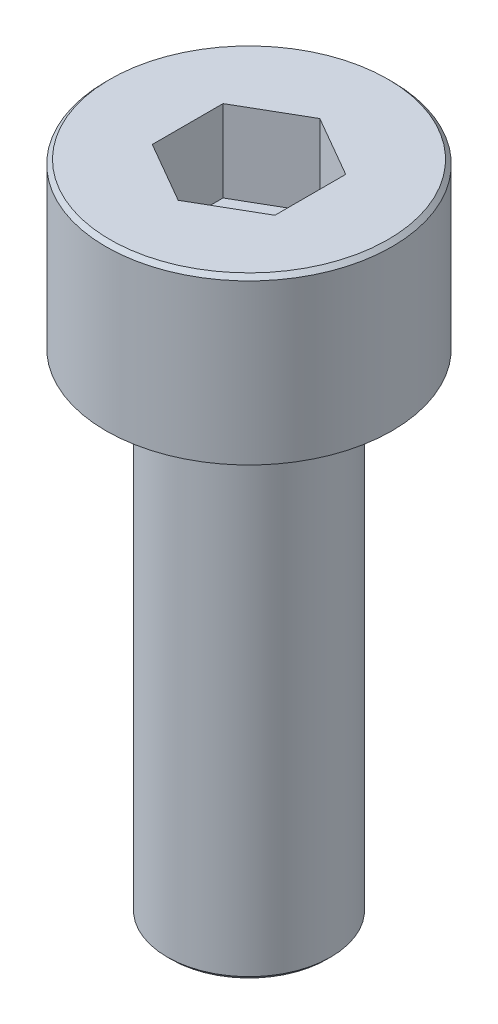
SolidWorks part; units mm, degrees
material "AISI 316, barra ricotta (SS)"
ref_plane "Piano frontale" through (0, 0, 0) normal (0, 0, 1) x (1, 0, 0)
ref_plane "Piano superiore" through (0, 0, 0) normal (0, 1, 0) x (1, 0, 0)
ref_plane "Piano destro" through (0, 0, 0) normal (1, 0, 0) x (0, 0, -1)
sketch "Schizzo1" plane through (0, 0, 0) normal (0, 0, 1) x (1, 0, 0)
  line L0 (0, 0) -> (0, 4)
  line L1 (0, 4) -> (3.5, 4)
  line L2 (3.5, 4) -> (3.5, 0)
  line L3 (3.5, 0) -> (2, 0)
  line L4 (2, 0) -> (2, -12)
  line L5 (2, -12) -> (0, -12)
  line L6 (0, -12) -> (0, 0)
  line L7 (0, 28.3885) -> (0, -27.6749) construction
  dimension "D1" = 4
  dimension "D2" = 4
  dimension "D3" = 7
  dimension "D4" = 12
revolve "Rivoluzione1" add sketch "Schizzo1" angle 360 about L7
chamfer "Smusso1" distance 0.1 angle 45 2 edges at (0, 4, 3.5) (0, -12, 2)
sketch "Schizzo2" plane through (0, 4, 0) normal (0, 1, 0) x (1, 0, 0)
  line L1 (0, 1.7321) -> (-1.5, 0.866)
  line L2 (-1.5, 0.866) -> (-1.5, -0.866)
  line L3 (-1.5, -0.866) -> (0, -1.7321)
  line L4 (0, -1.7321) -> (1.5, -0.866)
  line L5 (1.5, -0.866) -> (1.5, 0.866)
  line L6 (1.5, 0.866) -> (0, 1.7321)
  circle A0 centre (0, 0) radius 1.5 construction
  dimension "D1" = 3
extrude "Taglio-Estrusione1" cut sketch "Schizzo2" against normal blind 2
